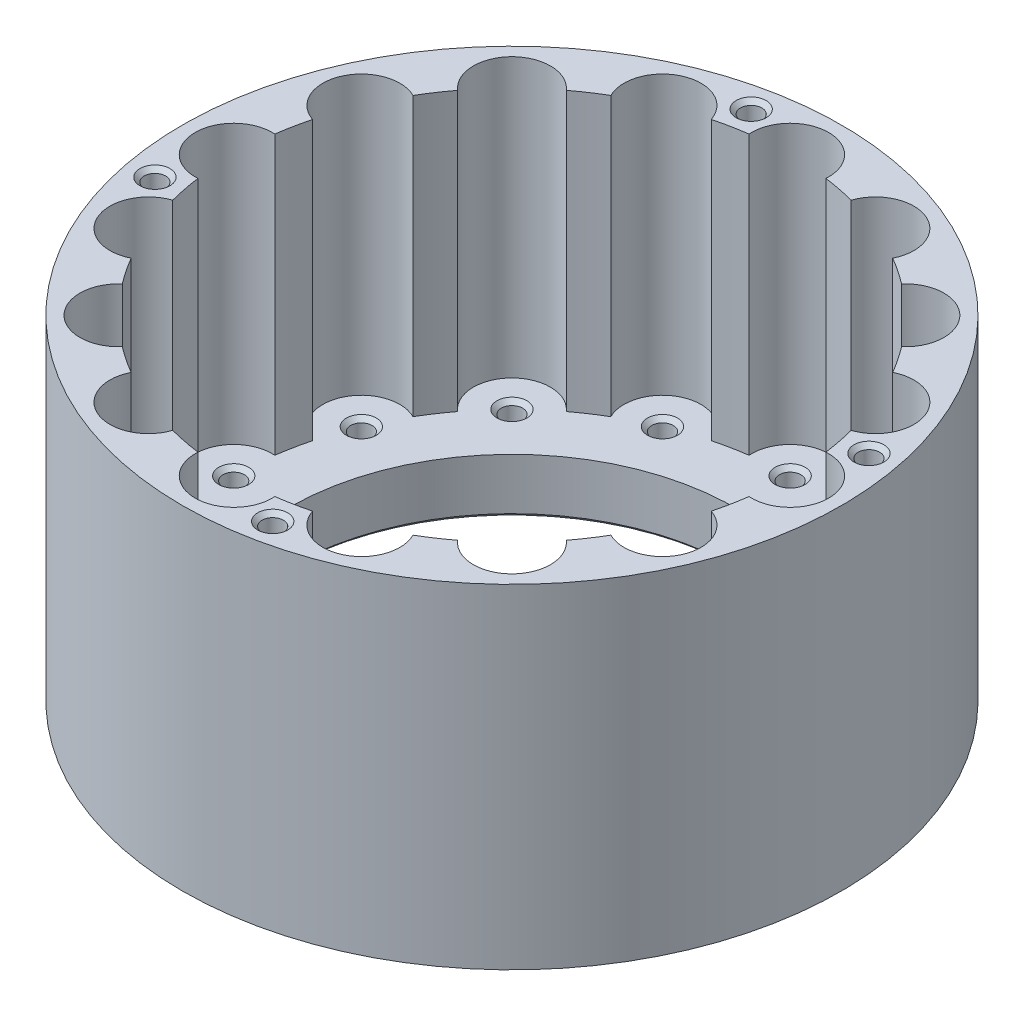
SolidWorks part; units mm, degrees
ref_plane "Ebene vorne" through (0, 0, 0) normal (0, 0, 1) x (1, 0, 0)
ref_plane "Ebene oben" through (0, 0, 0) normal (0, 1, 0) x (1, 0, 0)
ref_plane "Ebene rechts" through (0, 0, 0) normal (1, 0, 0) x (0, 0, -1)
sketch "Skizze1" plane through (0, 0, 0) normal (0, 1, 0) x (1, 0, 0)
  circle A0 centre (0, 0) radius 38.5
  dimension "D1" = 77
extrude "Aufsatz-Linear austragen1" add sketch "Skizze1" along normal blind 39
sketch "Skizze2" plane through (0, 39, 0) normal (0, 1, 0) x (1, 0, 0)
  arc A4 (-25.935, 19.5863) -> (-28.0203, 16.4655) centre (0, 0) ccw construction
  arc A5 (4.4892, 32.1885) -> (-4.4892, 32.1885) centre (0, 32.5) ccw
  arc A6 (16.4655, 28.0203) -> (8.1705, 31.4562) centre (12.4372, 30.0261) ccw
  arc A7 (25.935, 19.5863) -> (19.5863, 25.935) centre (22.981, 22.981) ccw
  arc A8 (31.4562, 8.1705) -> (28.0203, 16.4655) centre (30.0261, 12.4372) ccw
  arc A9 (32.1885, -4.4892) -> (32.1885, 4.4892) centre (32.5, 0) ccw
  arc A10 (28.0203, -16.4655) -> (31.4562, -8.1705) centre (30.0261, -12.4372) ccw
  arc A11 (19.5863, -25.935) -> (25.935, -19.5863) centre (22.981, -22.981) ccw
  arc A12 (8.1705, -31.4562) -> (16.4655, -28.0203) centre (12.4372, -30.0261) ccw
  arc A13 (-4.4892, -32.1885) -> (4.4892, -32.1885) centre (0, -32.5) ccw
  arc A14 (-16.4655, -28.0203) -> (-8.1705, -31.4562) centre (-12.4372, -30.0261) ccw
  arc A15 (-25.935, -19.5863) -> (-19.5863, -25.935) centre (-22.981, -22.981) ccw
  arc A16 (-31.4562, -8.1705) -> (-28.0203, -16.4655) centre (-30.0261, -12.4372) ccw
  arc A17 (-32.1885, 4.4892) -> (-32.1885, -4.4892) centre (-32.5, 0) ccw
  arc A18 (-28.0203, 16.4655) -> (-31.4562, 8.1705) centre (-30.0261, 12.4372) ccw
  arc A19 (-19.5863, 25.935) -> (-25.935, 19.5863) centre (-22.981, 22.981) ccw
  arc A20 (-8.1705, 31.4562) -> (-16.4655, 28.0203) centre (-12.4372, 30.0261) ccw
  arc A21 (-25.935, 19.5863) -> (-28.0203, 16.4655) centre (0, 0) ccw
  arc A22 (-16.4655, 28.0203) -> (-19.5863, 25.935) centre (0, 0) ccw construction
  arc A23 (-16.4655, 28.0203) -> (-19.5863, 25.935) centre (0, 0) ccw
  arc A24 (-4.4892, 32.1885) -> (-8.1705, 31.4562) centre (0, 0) ccw construction
  arc A25 (-4.4892, 32.1885) -> (-8.1705, 31.4562) centre (0, 0) ccw
  arc A26 (8.1705, 31.4562) -> (4.4892, 32.1885) centre (0, 0) ccw construction
  arc A27 (8.1705, 31.4562) -> (4.4892, 32.1885) centre (0, 0) ccw
  arc A28 (19.5863, 25.935) -> (16.4655, 28.0203) centre (0, 0) ccw construction
  arc A29 (19.5863, 25.935) -> (16.4655, 28.0203) centre (0, 0) ccw
  arc A30 (28.0203, 16.4655) -> (25.935, 19.5863) centre (0, 0) ccw construction
  arc A31 (28.0203, 16.4655) -> (25.935, 19.5863) centre (0, 0) ccw
  arc A32 (32.1885, 4.4892) -> (31.4562, 8.1705) centre (0, 0) ccw construction
  arc A33 (32.1885, 4.4892) -> (31.4562, 8.1705) centre (0, 0) ccw
  arc A34 (31.4562, -8.1705) -> (32.1885, -4.4892) centre (0, 0) ccw construction
  arc A35 (31.4562, -8.1705) -> (32.1885, -4.4892) centre (0, 0) ccw
  arc A36 (25.935, -19.5863) -> (28.0203, -16.4655) centre (0, 0) ccw construction
  arc A37 (25.935, -19.5863) -> (28.0203, -16.4655) centre (0, 0) ccw
  arc A38 (16.4655, -28.0203) -> (19.5863, -25.935) centre (0, 0) ccw construction
  arc A39 (16.4655, -28.0203) -> (19.5863, -25.935) centre (0, 0) ccw
  arc A40 (4.4892, -32.1885) -> (8.1705, -31.4562) centre (0, 0) ccw construction
  arc A41 (4.4892, -32.1885) -> (8.1705, -31.4562) centre (0, 0) ccw
  arc A42 (-8.1705, -31.4562) -> (-4.4892, -32.1885) centre (0, 0) ccw construction
  arc A43 (-8.1705, -31.4562) -> (-4.4892, -32.1885) centre (0, 0) ccw
  arc A44 (-19.5863, -25.935) -> (-16.4655, -28.0203) centre (0, 0) ccw construction
  arc A45 (-19.5863, -25.935) -> (-16.4655, -28.0203) centre (0, 0) ccw
  arc A46 (-28.0203, -16.4655) -> (-25.935, -19.5863) centre (0, 0) ccw construction
  arc A47 (-28.0203, -16.4655) -> (-25.935, -19.5863) centre (0, 0) ccw
  arc A48 (-32.1885, -4.4892) -> (-31.4562, -8.1705) centre (0, 0) ccw construction
  arc A49 (-32.1885, -4.4892) -> (-31.4562, -8.1705) centre (0, 0) ccw
  arc A50 (-31.4562, 8.1705) -> (-32.1885, 4.4892) centre (0, 0) ccw construction
  arc A51 (-31.4562, 8.1705) -> (-32.1885, 4.4892) centre (0, 0) ccw
  point P37 (-28.0125, 16.4788)
  dimension "D1" = 65
  dimension "D2" = 9
extrude "Schnitt-Linear austragen1" cut sketch "Skizze2" against normal blind 32.5
sketch "Skizze3" plane through (0, 0, 0) normal (0, -1, 0) x (1, 0, 0)
  circle A0 centre (0, 0) radius 26.075
  dimension "D1" = 52.15
extrude "Schnitt-Linear austragen2" cut sketch "Skizze3" against normal through all
hole_wizard "Ø2.5 (2.5) Durchmesser Bohrung1" positions "Skizze4" profile "Skizze5" hole size "Ø2.5" standard "DIN" end condition through all
sketch "Skizze4" plane through (0, 6.5, 0) normal (0, 1, 0) x (1, 0, 0)
  point P0 (0, 32.5)
  point P13 (12.4372, 30.0261)
  point P14 (22.981, 22.981)
  point P15 (30.0261, 12.4372)
  point P16 (32.5, 0)
  point P17 (30.0261, -12.4372)
  point P18 (22.981, -22.981)
  point P19 (12.4372, -30.0261)
  point P20 (0, -32.5)
  point P21 (-12.4372, -30.0261)
  point P22 (-22.981, -22.981)
  point P23 (-30.0261, -12.4372)
  point P24 (-32.5, 0)
  point P25 (-30.0261, 12.4372)
  point P26 (-22.981, 22.981)
  point P27 (-12.4372, 30.0261)
sketch "Skizze5" plane through (0, 6.5, -32.5) normal (1, 0, 0) x (0, 0, 1)
  line L0 (0, 0) -> (0, 6.5)
  line L1 (0, 6.5) -> (1.25, 6.5)
  line L2 (1.25, 6.5) -> (1.25, 0.5)
  line L3 (1.25, 0.5) -> (1.75, 0)
  line L5 (1.75, 0) -> (0, 0)
  line L6 (-1.25, 0.5) -> (-1.75, 0) construction
  line L11 (0, -6.35) -> (0, 107.95) construction
  dimension "Bohrerdurchmesser" = 2.5
  dimension "Bohrungstiefe" = 6.5
  dimension "Senkdurchmesser2 (Oben)" = 3.5
  dimension "Senkwinkel2 (Oben)" = 90
hole_wizard "Ø2.5 (2.5) Durchmesser Bohrung2" positions "Skizze6" profile "Skizze8" hole size "Ø2.5" standard "DIN"
sketch "Skizze6" plane through (0, 39, 0) normal (0, 1, 0) x (1, 0, 0)
  circle A0 centre (0, 0) radius 35.5 construction
  point P5 (-6.8792, 34.8271)
  point P15 (34.8271, 6.8792)
  point P17 (6.8792, -34.8271)
  point P19 (-34.8271, -6.8792)
  point P21 (0, 0)
  point P22 (19.7622, 29.4908)
  point P23 (0, 0)
  point P24 (29.4908, -19.7622)
  point P25 (0, 0)
  point P26 (-19.7622, -29.4908)
  point P27 (0, 0)
  point P28 (-29.4908, 19.7622)
  dimension "D1" = 71
  dimension "D2" = 8
sketch "Skizze8" plane through (-34.8271, 39, 6.8792) normal (1, 0, 0) x (0, 0, 1)
  line L0 (0, 0) -> (0, 15.7511)
  line L1 (0, 15.7511) -> (1.25, 15)
  line L2 (1.25, 15) -> (1.25, 0.5)
  line L3 (1.25, 0.5) -> (1.75, 0)
  line L5 (1.75, 0) -> (0, 0)
  line L6 (-1.25, 0.5) -> (-1.75, 0) construction
  line L10 (0, 15.7511) -> (-1.25, 15) construction
  line L11 (0, -6.35) -> (0, 107.95) construction
  dimension "Bohrerdurchmesser" = 2.5
  dimension "Bohrungstiefe" = 15
  dimension "Senkdurchmesser2 (Oben)" = 3.5
  dimension "Senkwinkel2 (Oben)" = 90
  dimension "Spitzenwinkel" = 118
chamfer "Fase1" distance 0.5 angle 45 1 edges at (0, 0, -26.075)
